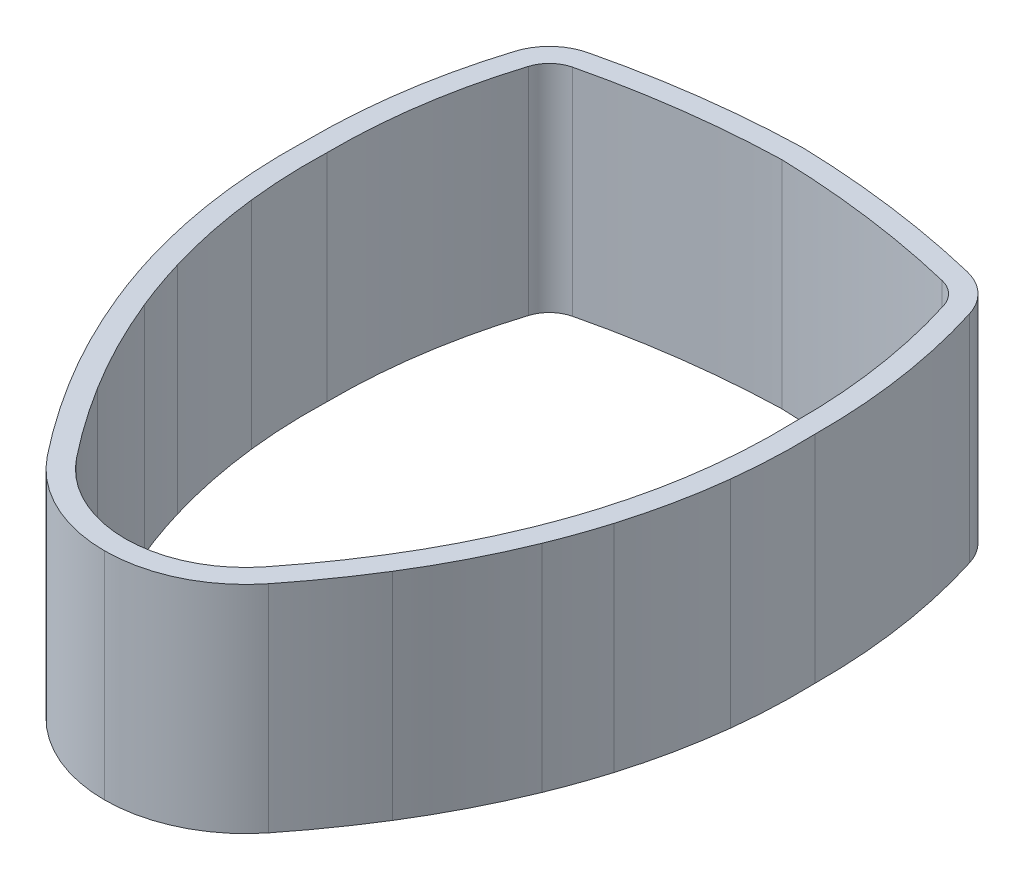
SolidWorks part; units mm, degrees
ref_plane "Front Plane" through (0, 0, 0) normal (0, 0, 1) x (1, 0, 0)
ref_plane "Top Plane" through (0, 0, 0) normal (0, 1, 0) x (1, 0, 0)
ref_plane "Right Plane" through (0, 0, 0) normal (1, 0, 0) x (0, 0, -1)
sketch "Sketch1" plane through (0, 0, 0) normal (0, 1, 0) x (1, 0, 0)
  line L0 (0, -18.0911) -> (0, 18.0911) construction
  arc A0 (0, 98.5) -> (-27.9743, 94.7786) centre (3.8473, -37.4251) ccw construction
  arc A1 (-27.9743, 94.7786) -> (-30.8555, 92.085) centre (-27.0383, 90.8897) ccw construction
  arc A2 (-30.8555, 92.085) -> (-35, 66.1114) centre (55.8665, 64.9296) ccw construction
  arc A3 (-35, 66.1114) -> (-34.3478, 53.8466) centre (57.9257, 64.9028) ccw construction
  arc A4 (-34.3478, 53.8466) -> (-31.3839, 39.3715) centre (54.4341, 64.4845) ccw construction
  arc A5 (-31.3839, 39.3715) -> (-28.8854, 32.1387) centre (-209.5449, -26.223) cw construction
  arc A6 (-28.8854, 32.1387) -> (-21.8926, 17.7497) centre (69.472, 71.0445) ccw construction
  arc A7 (-21.8926, 17.7497) -> (-13.5993, 6.341) centre (501.5045, 389.5049) ccw construction
  arc A8 (-13.5993, 6.341) -> (0, 0) centre (0.0442, 17.8482) ccw construction
  arc A18 (0, 99.2937) -> (-28.1678, 95.5484) centre (3.8424, -37.3986) ccw
  arc A19 (-28.1678, 95.5484) -> (-31.6153, 92.3145) centre (-27.0383, 90.8897) ccw
  arc A20 (-31.6153, 92.3145) -> (-35.588, 65.5782) centre (50.8986, 66.3908) ccw
  arc A21 (-35.588, 65.5782) -> (-35.0957, 53.5805) centre (45.701, 62.9048) ccw
  arc A22 (-32.1776, 39.3849) -> (-29.4179, 31.5502) centre (50.6019, 64.1395) ccw
  arc A23 (-29.4179, 31.5502) -> (-21.9777, 16.9605) centre (60.0872, 68.0025) ccw
  arc A24 (-21.9777, 16.9605) -> (-14.3725, 6.1618) centre (76.1699, 78.0054) ccw
  arc A25 (-14.3725, 6.1618) -> (0, -0.7938) centre (0.0258, 17.5866) ccw
  arc A26 (-35.0957, 53.5805) -> (-32.1776, 39.3849) centre (46.9586, 63.05) ccw
  arc A27 (0, 99.2937) -> (28.1678, 95.5484) centre (-3.8424, -37.3986) cw
  arc A28 (28.1678, 95.5484) -> (31.6153, 92.3145) centre (27.0383, 90.8897) cw
  arc A29 (31.6153, 92.3145) -> (35.588, 65.5782) centre (-50.8986, 66.3908) cw
  arc A30 (35.588, 65.5782) -> (35.0957, 53.5805) centre (-45.701, 62.9048) cw
  arc A31 (32.1776, 39.3849) -> (29.4179, 31.5502) centre (-50.6019, 64.1395) cw
  arc A32 (35.0957, 53.5805) -> (32.1776, 39.3849) centre (-46.9586, 63.05) cw
  arc A33 (29.4179, 31.5502) -> (21.9777, 16.9605) centre (-60.0872, 68.0025) cw
  arc A34 (21.9777, 16.9605) -> (14.3725, 6.1618) centre (-76.1699, 78.0054) cw
  arc A35 (14.3725, 6.1618) -> (0, -0.7938) centre (-0.0258, 17.5866) cw
  point P35 (-30.892, 35.4343)
  point P36 (-30.0982, 35.7677)
  point P66 (-35.5635, 59.5702)
  point P67 (-14.1815, 98.1547)
  point P68 (-14.084, 97.367)
  point P69 (-30.3179, 94.3859)
  point P70 (-29.77, 93.8116)
  point P71 (-34.6526, 79.1025)
  point P72 (-33.8724, 79.2489)
  point P74 (-34.8768, 59.9682)
  point P79 (-26.0074, 24.0975)
  point P80 (-25.6614, 24.8118)
  point P81 (-18.3295, 11.4524)
  point P82 (-17.7773, 12.0226)
  point P83 (-7.981, 1.0418)
  point P84 (-7.4984, 1.672)
  point P111 (-33.9486, 46.4186)
  point P112 (-33.1654, 46.5477)
  dimension "D18" = 0.7938
  dimension "D21" = 0.7938
  dimension "D2" = 0.7937
  dimension "D3" = 0.7938
  dimension "D4" = 0.7937
  dimension "D5" = 0.7937
  dimension "D6" = 0.7937
  dimension "D7" = 0.7938
  dimension "D8" = 0.7938
  dimension "D9" = 0.7937
  dimension "D10" = 0.7937
  dimension "D11" = 0.7937
  dimension "D12" = 0.7937
  dimension "D13" = 0.7938
  dimension "D14" = 0.7938
  dimension "D15" = 0.7938
  dimension "D17" = 0.7938
  dimension "D19" = 0.7937
  dimension "D20" = 0.7937
extrude "Extrude-Thin1" add sketch "Sketch1" along normal blind 32.893 thin contours A35 A34 A33 A31 A32 A30 A29 A28 A27 A18 A19 A20 A21 A26 A22 A23 A24 A25
